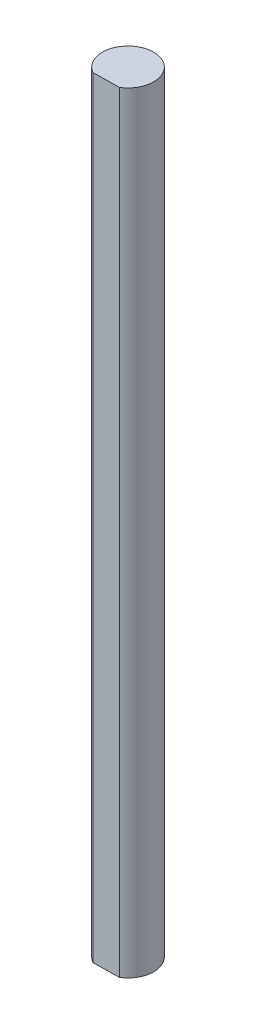
SolidWorks part; units mm, degrees
ref_plane "Plan de face" through (0, 0, 0) normal (0, 0, 1) x (1, 0, 0)
ref_plane "Plan de dessus" through (0, 0, 0) normal (0, 1, 0) x (1, 0, 0)
ref_plane "Plan de droite" through (0, 0, 0) normal (1, 0, 0) x (0, 0, -1)
sketch "Esquisse1" plane through (0, 0, 0) normal (0, 1, 0) x (1, 0, 0)
  circle A0 centre (0, 0) radius 2
extrude "Boss.-Extru.1" add sketch "Esquisse1" along normal blind 60
sketch "Esquisse2" plane through (0, 60, 0) normal (0, 1, 0) x (1, 0, 0)
  circle A0 centre (0, 0) radius 2
sketch "Esquisse3" plane through (0, 60, 0) normal (0, 1, 0) x (1, 0, 0)
  line L0 (-0.9792, -1.7439) -> (1.0364, -1.7105)
  circle A0 centre (0, 0) radius 2
  circle M1 centre (0, 0) radius 2
extrude "Enlèv. mat.-Extru.1" cut sketch "Esquisse3" against normal through all contours L0 M1
